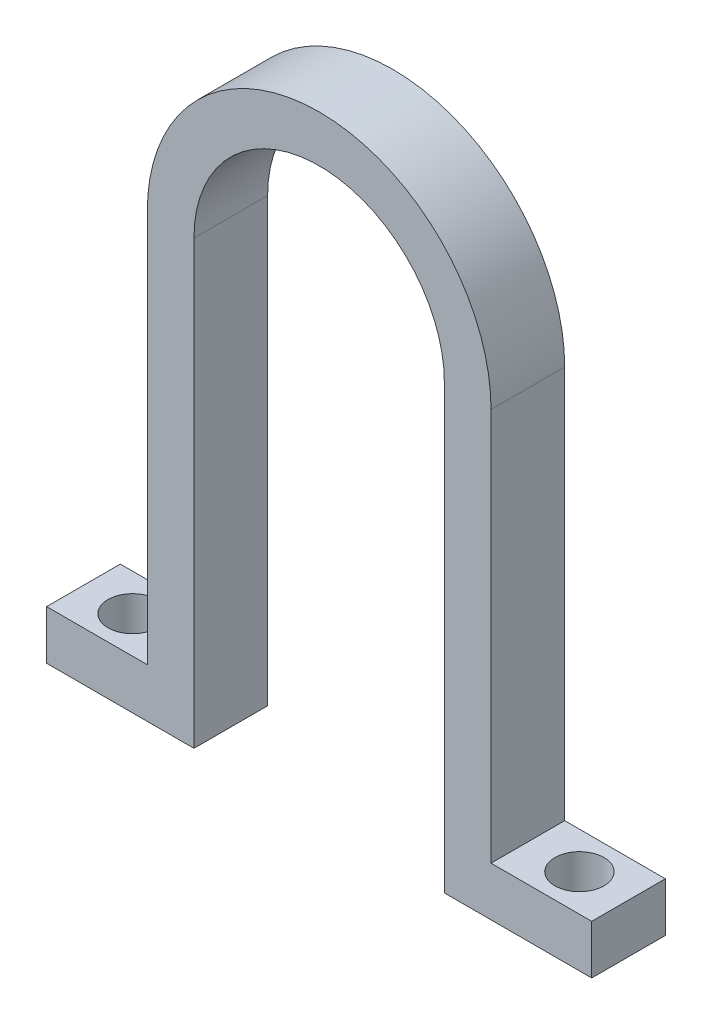
SolidWorks part; units mm, degrees
ref_plane "Front Plane" through (0, 0, 0) normal (0, 0, 1) x (1, 0, 0)
ref_plane "Top Plane" through (0, 0, 0) normal (0, 1, 0) x (1, 0, 0)
ref_plane "Right Plane" through (0, 0, 0) normal (1, 0, 0) x (0, 0, -1)
sketch "Sketch1" plane through (0, 0, 0) normal (0, 0, 1) x (1, 0, 0)
  line L4 (55.5, -90) -> (55.5, -80)
  line L6 (25.5, -90) -> (55.5, -90)
  line L7 (25.5, 0) -> (25.5, -90)
  line L8 (25.5, 0) -> (40.1852, 0) construction
  line L9 (35, 0) -> (35, -80)
  line L10 (55.5, -80) -> (35, -80)
  line L11 (0, 0) -> (0, -30.0197) construction
  line L12 (-55.5, -90) -> (-55.5, -80)
  line L13 (-35, 0) -> (-35, -80)
  line L14 (-55.5, -80) -> (-35, -80)
  line L15 (-25.5, -90) -> (-55.5, -90)
  line L16 (-25.5, 0) -> (-25.5, -90)
  arc A0 (25.5, 0) -> (-25.5, 0) centre (0, 0) ccw
  arc A1 (35, 0) -> (-35, 0) centre (0, 0) ccw
  dimension "D1" = 25.5
  dimension "D2" = 35
  dimension "D3" = 10
  dimension "D4" = 30
  dimension "D6" = 90
extrude "Boss-Extrude1" add sketch "Sketch1" along normal blind 15
sketch "Sketch3" plane through (0, -90, 0) normal (0, -1, 0) x (1, 0, 0)
  line L3 (-55.5, 0) -> (-25.5, 0) construction
  line L4 (-55.5, 15) -> (-55.5, 0) construction
  line L5 (0, 0) -> (0, 31.5586) construction
  circle A0 centre (-45.5, 7.5) radius 5
  circle A1 centre (45.5, 7.5) radius 5
  dimension "D1" = 7.5
  dimension "D2" = 10
extrude "Cut-Extrude2" cut sketch "Sketch3" against normal through all
